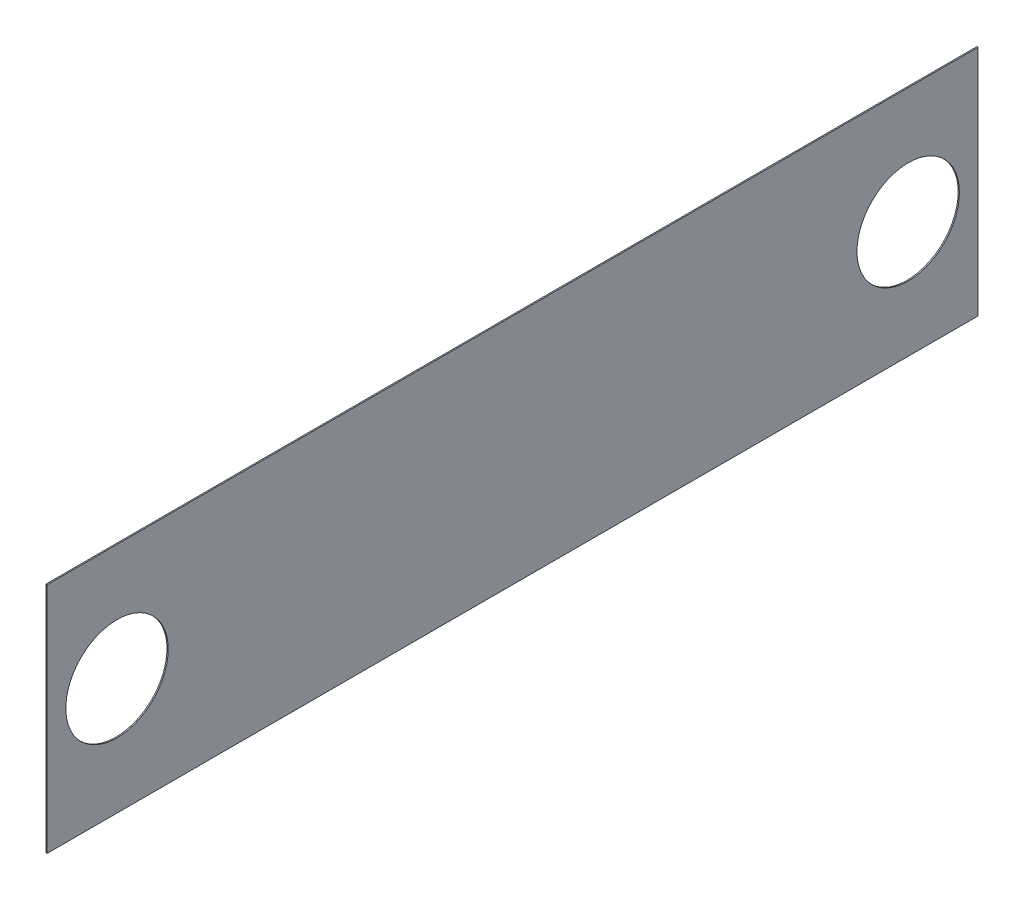
SolidWorks part; units mm, degrees
material "Low Carbon Steel"
ref_plane "Front Plane" through (0, 0, 0) normal (0, 0, 1) x (1, 0, 0)
ref_plane "Top Plane" through (0, 0, 0) normal (0, 1, 0) x (1, 0, 0)
ref_plane "Right Plane" through (0, 0, 0) normal (1, 0, 0) x (0, 0, -1)
sketch "Sketch1" plane through (0, 0, 0) normal (1, 0, 0) x (0, 0, -1)
  line L0 (-50, -12.5) -> (50, 12.5) construction
  line L1 (-50, 12.5) -> (50, 12.5)
  line L2 (-50, 12.5) -> (-50, -12.5)
  line L3 (-50, -12.5) -> (50, -12.5)
  line L4 (50, 12.5) -> (50, -12.5)
  dimension "D1" = 100
  dimension "D2" = 25
extrude "Boss-Extrude1" add sketch "Sketch1" along normal blind 0.127
hole_wizard "M10 Clearance Hole1" positions "Sketch2" profile "Sketch3" hole size "M10" standard "Peddi DIN" end condition through all
sketch "Sketch2" plane through (0.127, 0, 0) normal (1, 0, 0) x (0, 0, -1)
  line L0 (42.5, 0) -> (-42.5, 0) construction
  point P0 (-42.5, 0)
  point P2 (42.5, 0)
  dimension "D1" = 85
sketch "Sketch3" plane through (0.127, 0, 42.5) normal (0, 1, 0) x (0, 0, -1)
  line L0 (0, 0) -> (0, 0.127)
  line L1 (0, 0.127) -> (5.5, 0.127)
  line L2 (5.5, 0.127) -> (5.5, 0)
  line L5 (5.5, 0) -> (0, 0)
  line L11 (0, -6.35) -> (0, 107.95) construction
  dimension "Thru Hole Dia." = 11
  dimension "Thru Hole Depth" = 0.127
other "Freeze***"
